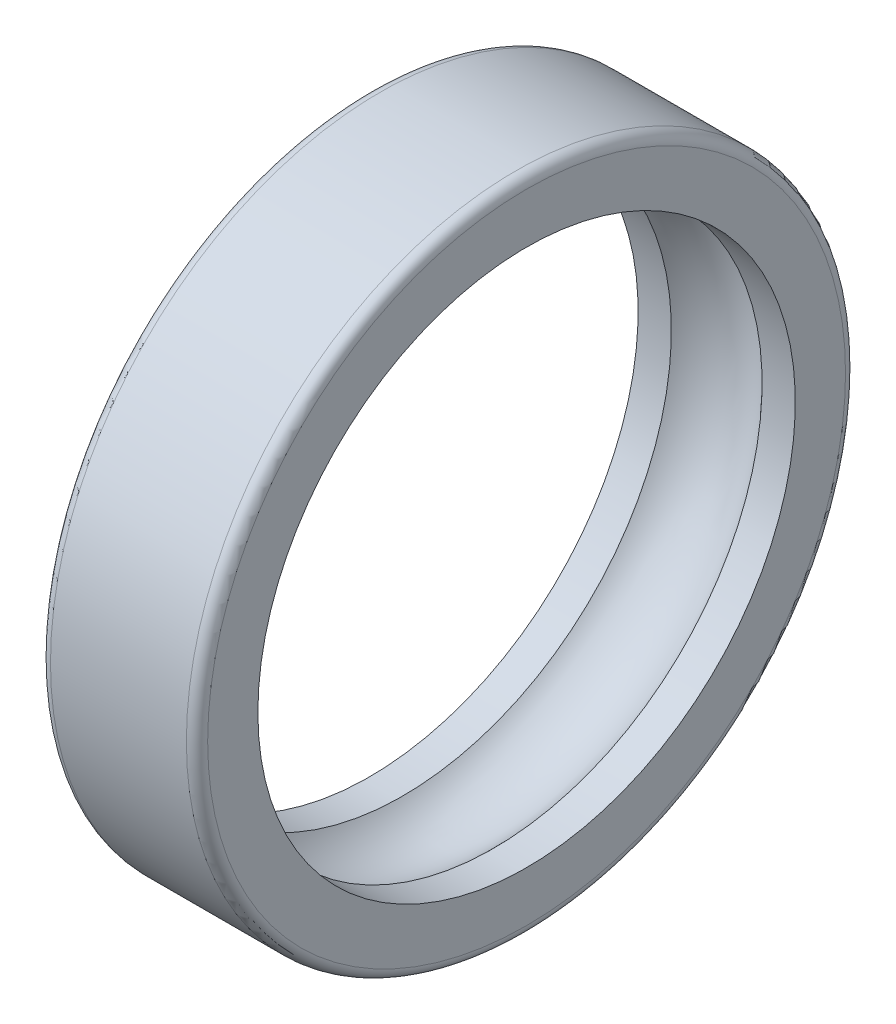
SolidWorks part; units mm, degrees
ref_plane "Front Plane" through (0, 0, 0) normal (0, 0, 1) x (1, 0, 0)
ref_plane "Top Plane" through (0, 0, 0) normal (0, 1, 0) x (1, 0, 0)
ref_plane "Right Plane" through (0, 0, 0) normal (1, 0, 0) x (0, 0, -1)
sketch "Sketch1" plane through (0, 0, 0) normal (0, 0, 1) x (1, 0, 0)
  line L0 (-124.4266, 0) -> (267.3394, 0) construction
  line L1 (0, 530) -> (0, 0) construction
  line L2 (155, 530) -> (89.4427, 530)
  line L3 (155, 530) -> (155, 650)
  line L4 (155, 650) -> (-155, 650)
  line L5 (-155, 530) -> (-155, 650)
  line L6 (155, 530) -> (-155, 650) construction
  line L7 (155, 650) -> (-155, 530) construction
  line L8 (-89.4427, 530) -> (-155, 530)
  arc A0 (-89.4427, 530) -> (89.4427, 530) centre (0, 450) cw
  point P3 (0, 590)
  dimension "D4" = 80
  dimension "D5" = 120
  dimension "D1" = 310
  dimension "D2" = 530
  dimension "D3" = 650
revolve "Revolve1" add sketch "Sketch1" angle 360 about L0
fillet "Fillet2" radius 21 2 edges at (155, 0, 650) (-155, 0, 650)
